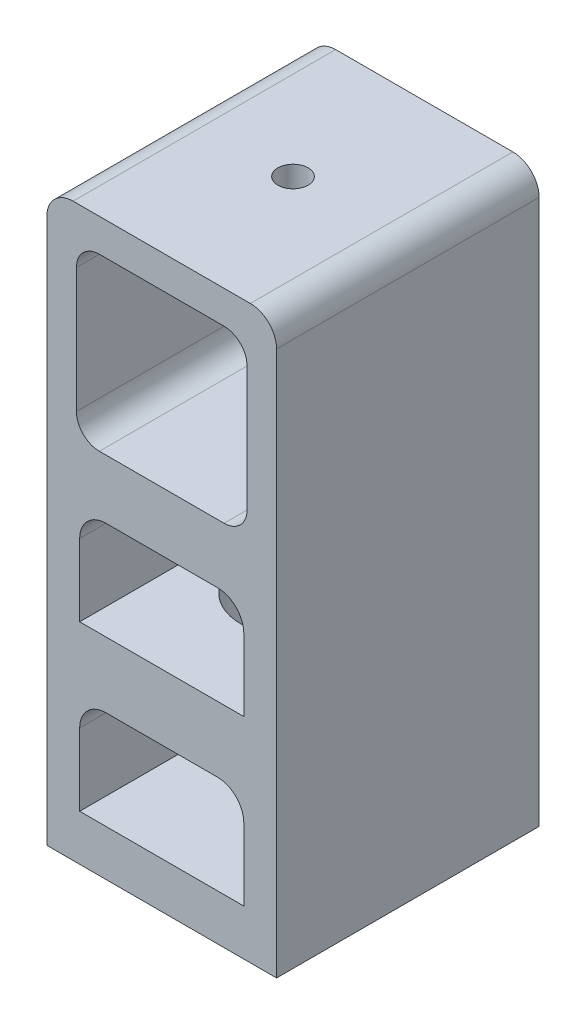
SolidWorks part; units mm, degrees
ref_plane "Front Plane" through (0, 0, 0) normal (0, 0, 1) x (1, 0, 0)
ref_plane "Top Plane" through (0, 0, 0) normal (0, 1, 0) x (1, 0, 0)
ref_plane "Right Plane" through (0, 0, 0) normal (1, 0, 0) x (0, 0, -1)
sketch "Sketch1" plane through (0, 0, 0) normal (0, 0, 1) x (1, 0, 0)
  line L0 (17.5, 35) -> (17.5, 0) construction
  line L1 (0, 0) -> (35, 0)
  line L2 (0, 0) -> (0, 35)
  line L3 (0, 35) -> (35, 35)
  line L4 (35, 0) -> (35, 35)
  line L5 (4.5, 30) -> (30.5, 30)
  line L6 (4.5, 30) -> (4.5, 4)
  line L7 (4.5, 4) -> (30.5, 4)
  line L8 (30.5, 30) -> (30.5, 4)
  line L10 (0, 0) -> (35, 0)
  line L11 (0, 0) -> (0, -30)
  line L12 (0, -30) -> (35, -30)
  line L13 (35, 0) -> (35, -30)
  line L14 (5, -20) -> (30, -20)
  line L15 (5, -20) -> (5, -5)
  line L16 (5, -5) -> (30, -5)
  line L17 (30, -20) -> (30, -5)
  line L18 (0, -30) -> (35, -30)
  dimension "D1" = 26
  dimension "D2" = 26
  dimension "D3" = 35
  dimension "D4" = 35
  dimension "D5" = 5
  dimension "D6" = 30
  dimension "D7" = 5
  dimension "D8" = 10
  dimension "D9" = 15
extrude "Boss-Extrude2" add sketch "Sketch1" along normal blind 40 contours L13 L10 L1 L11 L12 | L0 L3 L2 L1 L7 L6 L5 | L3 L0 L5 L8 L7 L10 L4
fillet "Fillet3" radius 3.5 4 edges at (4.5, 30, 20) (30.5, 30, 20) (30.5, 4, 20) (4.5, 4, 20)
fillet "Fillet4" radius 4 2 edges at (0, 35, 20) (35, 35, 20)
sketch "Sketch6" plane through (0, 35, 0) normal (0, 1, 0) x (1, 0, 0)
  line L0 (17.5, 0) -> (17.5, -40) construction
  line L1 (4, 0) -> (31, 0) construction
  line L2 (4, -40) -> (31, -40) construction
  line L3 (4, -20) -> (31, -20) construction
  line L4 (4, 0) -> (4, -40) construction
  line L5 (31, -40) -> (31, 0) construction
  circle A0 centre (17.5, -20) radius 2.3
extrude "Cut-Extrude5" cut sketch "Sketch6" against normal up to surface (5 mm away) up to face at (17.5, 30, 20)
sketch "Sketch7" plane through (0, -20, 0) normal (0, 1, 0) x (1, 0, 0)
  line L0 (17.5, 0) -> (17.5, -40) construction
  line L1 (5, 0) -> (30, 0) construction
  line L2 (5, -40) -> (30, -40) construction
  line L3 (0, -20) -> (35, -20) construction
  line L4 (0, -40) -> (0, 0) construction
  line L5 (35, -40) -> (35, 0) construction
  circle A0 centre (17.5, -20) radius 8
  dimension "D1" = 16
sketch "Sketch9" plane through (0, 0, 40) normal (0, 0, 1) x (1, 0, 0)
  line L0 (30, -20) -> (30, -5) construction
  line L1 (0, -30) -> (35, -30)
  line L2 (0, -30) -> (0, -52)
  line L3 (0, -52) -> (35, -52)
  line L4 (35, -30) -> (35, -52)
  line L5 (5, -30) -> (30, -30)
  line L6 (5, -30) -> (5, -45)
  line L7 (5, -45) -> (30, -45)
  line L8 (30, -30) -> (30, -45)
  line L9 (5, -20) -> (5, -5) construction
  line M24 (0, -30) -> (35, -30)
  dimension "D1" = 7
  dimension "D2" = 15
extrude "Boss-Extrude3" add sketch "Sketch9" against normal up to surface (40 mm away) contours L8 L7 L6 L2 L3 L4 M24 up to face at (17.5, 17, 0)
extrude "Cut-Extrude8" cut sketch "Sketch7" against normal up to surface (10 mm away) contours A0 up to face at (17.5, -30, 20)
sketch "Sketch11" plane through (0, -45, 0) normal (0, 1, 0) x (1, 0, 0)
  line L0 (0, -20) -> (35, -20) construction
  line L1 (0, 0) -> (0, -40) construction
  line L2 (35, 0) -> (35, -40) construction
  line L3 (17.5, 0) -> (17.5, -40) construction
  line L4 (30, 0) -> (5, 0) construction
  line L5 (5, -40) -> (30, -40) construction
  circle A0 centre (17.5, -20) radius 6.25
  dimension "D1" = 12.5
extrude "Cut-Extrude9" cut sketch "Sketch11" against normal blind 4
sketch "Sketch12" plane through (0, -45, 0) normal (0, 1, 0) x (1, 0, 0)
  circle A0 centre (17.5, -20) radius 2.75
extrude "Cut-Extrude10" cut sketch "Sketch12" against normal through all
fillet "Fillet5" radius 4 4 edges at (30, -30, 20) (5, -30, 20) (30, -5, 20) (5, -5, 20)
